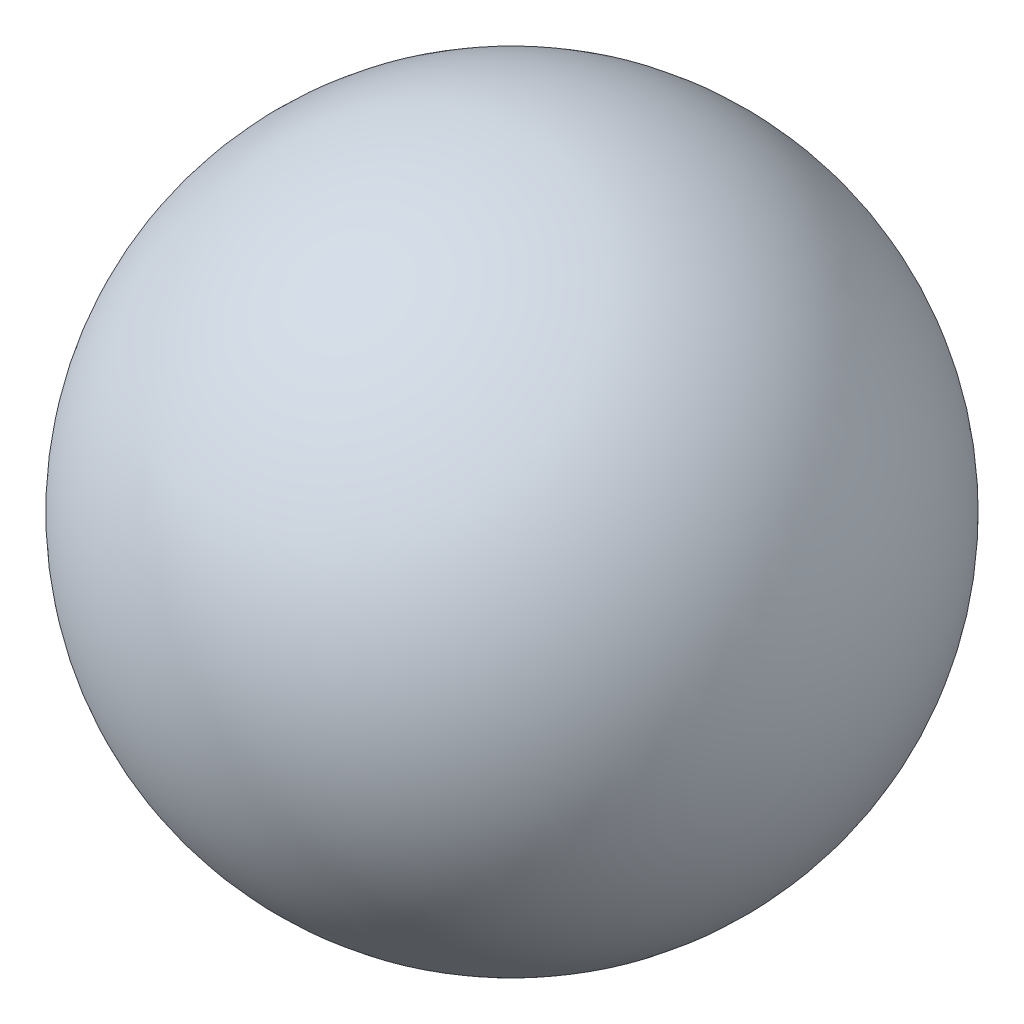
SolidWorks part; units mm, degrees
ref_plane "Front Plane" through (0, 0, 0) normal (0, 0, 1) x (1, 0, 0)
ref_plane "Top Plane" through (0, 0, 0) normal (0, 1, 0) x (1, 0, 0)
ref_plane "Right Plane" through (0, 0, 0) normal (1, 0, 0) x (0, 0, -1)
sketch "Sketch1" plane through (0, 0, 0) normal (0, 0, 1) x (1, 0, 0)
  line L0 (0, 232.8333) -> (0, 239.1833)
  line L1 (0, 74.0833) -> (0, 80.4333)
  arc A0 (0, 239.1833) -> (0, 74.0833) centre (0, 156.6333) ccw
  arc A1 (0, 232.8333) -> (0, 80.4333) centre (0, 156.6333) ccw
  dimension "D2" = 76.2
  dimension "D1" = 6.35
revolve "Revolve2" add sketch "Sketch1" angle 360 about L0
